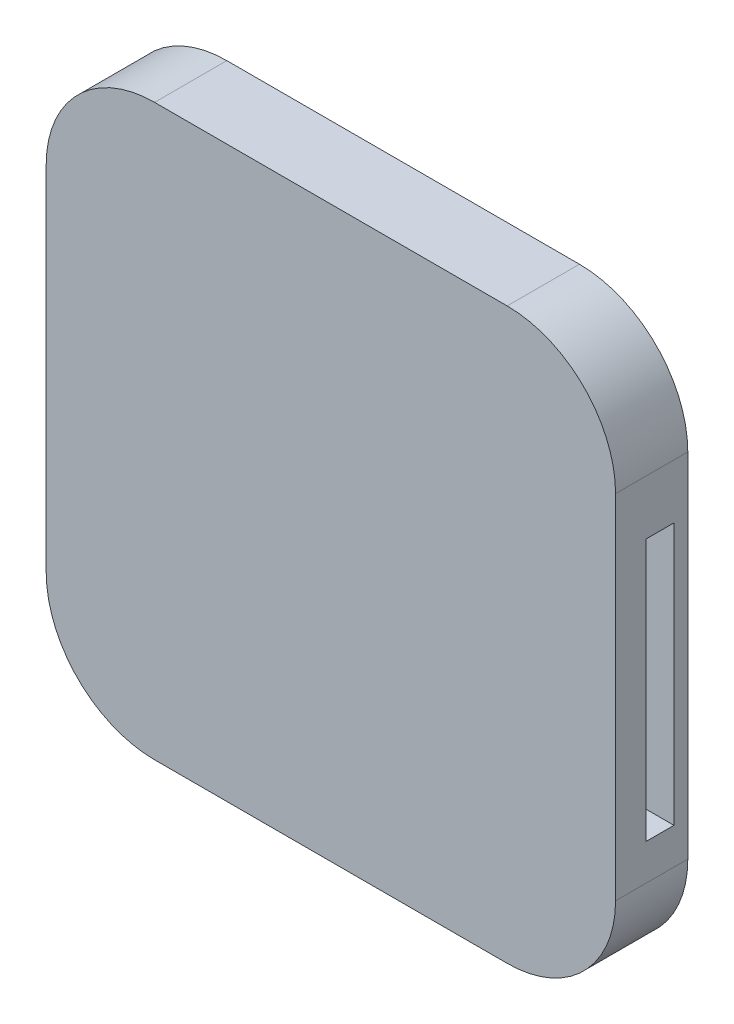
SolidWorks part; units mm, degrees
ref_plane "Front Plane" through (0, 0, 0) normal (0, 0, 1) x (1, 0, 0)
ref_plane "Top Plane" through (0, 0, 0) normal (0, 1, 0) x (1, 0, 0)
ref_plane "Right Plane" through (0, 0, 0) normal (1, 0, 0) x (0, 0, -1)
sketch "Sketch2" plane through (0, 0, 0) normal (0, 0, 1) x (1, 0, 0)
  line L1 (-29.1727, 34.1959) -> (70.9033, 34.1959)
  line L2 (-29.1727, 34.1959) -> (-29.1727, -65.8801)
  line L3 (-29.1727, -65.8801) -> (70.9033, -65.8801)
  line L4 (70.9033, 34.1959) -> (70.9033, -65.8801)
  dimension "D1" = 100.076
  dimension "D2" = 100.076
extrude "Boss-Extrude2" add sketch "Sketch2" along normal blind 12.7
fillet "Fillet1" radius 19.05 4 edges at (70.9033, -65.8801, 6.35) (-29.1727, -65.8801, 6.35) (70.9033, 34.1959, 6.35) (-29.1727, 34.1959, 6.35)
sketch "Sketch3" plane through (70.9033, 0, 0) normal (1, 0, 0) x (0, 0, -1)
  line L1 (-7.3812, 5.5642) -> (-2.433, 5.5642)
  line L2 (-7.3812, 5.5642) -> (-7.3812, -40.4756)
  line L3 (-7.3812, -40.4756) -> (-2.433, -40.4756)
  line L4 (-2.433, 5.5642) -> (-2.433, -40.4756)
extrude "Cut-Extrude1" cut sketch "Sketch3" against normal blind 9.906
